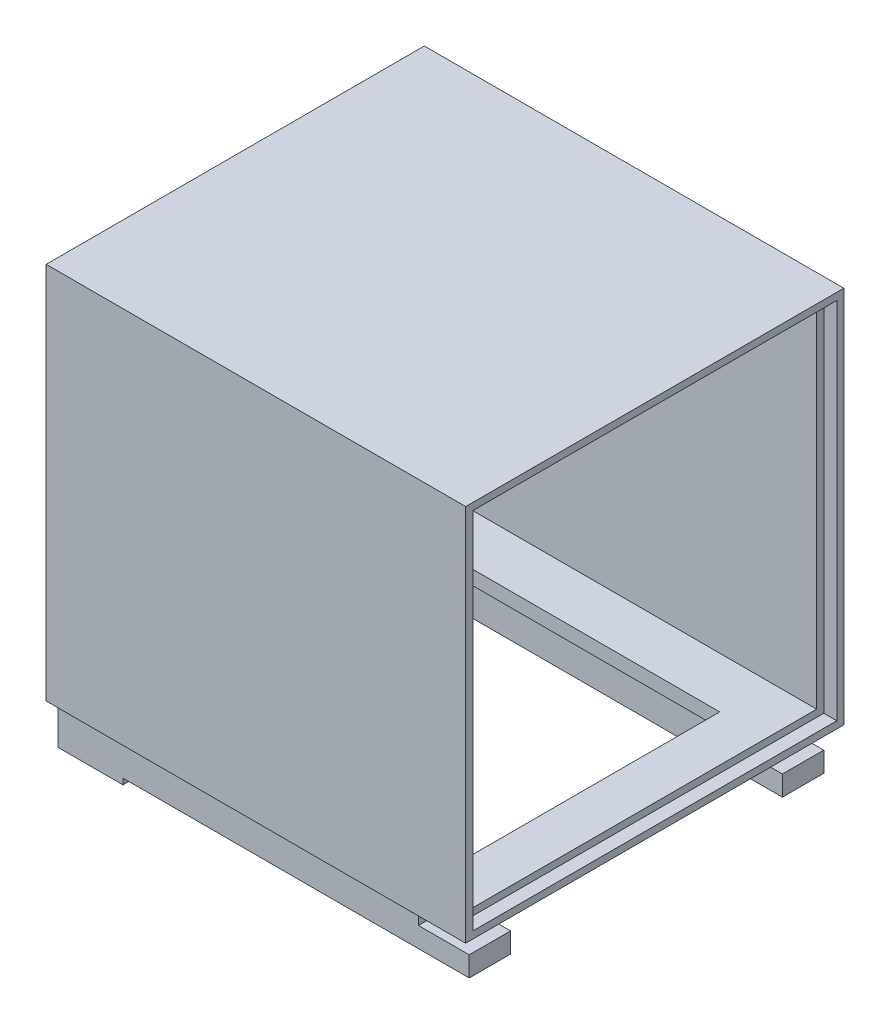
SolidWorks part; units mm, degrees
ref_plane "Front Plane" through (0, 0, 0) normal (0, 0, 1) x (1, 0, 0)
ref_plane "Top Plane" through (0, 0, 0) normal (0, 1, 0) x (1, 0, 0)
ref_plane "Right Plane" through (0, 0, 0) normal (1, 0, 0) x (0, 0, -1)
sketch "Sketch1" plane through (0, 0, 0) normal (0, 1, 0) x (1, 0, 0)
  line L1 (0, 0) -> (355, 0)
  line L2 (0, 0) -> (0, 320)
  line L3 (0, 320) -> (355, 320)
  line L4 (355, 0) -> (355, 320)
  dimension "D1" = 355
  dimension "D2" = 320
extrude "Boss-Extrude1" add sketch "Sketch1" along normal blind 320
sketch "Sketch9" plane through (355, 0, 0) normal (1, 0, 0) x (0, 0, -1)
  line L0 (320, 320) -> (320, 0) construction
  line L1 (12, 308) -> (308, 308)
  line L2 (12, 308) -> (12, 12)
  line L3 (12, 12) -> (308, 12)
  line L4 (308, 308) -> (308, 12)
  line L5 (0, 320) -> (0, 0) construction
  line L6 (0, 320) -> (320, 320) construction
  line L7 (0, 0) -> (320, 0) construction
  dimension "D1" = 12
  dimension "D2" = 12
  dimension "D3" = 12
  dimension "D4" = 12
extrude "Cut-Extrude3" cut sketch "Sketch9" against normal blind 345
sketch "Sketch10" plane through (355, 0, 0) normal (1, 0, 0) x (0, 0, -1)
  line L0 (0, 320) -> (0, 0) construction
  line L1 (6, 314) -> (314, 314)
  line L2 (6, 314) -> (6, 6)
  line L3 (6, 6) -> (314, 6)
  line L4 (314, 314) -> (314, 6)
  line L5 (320, 320) -> (320, 0) construction
  line L6 (0, 320) -> (320, 320) construction
  line L7 (0, 0) -> (320, 0) construction
  dimension "D1" = 6
  dimension "D2" = 6
  dimension "D3" = 6
  dimension "D4" = 6
extrude "Cut-Extrude4" cut sketch "Sketch10" against normal blind 11
sketch "Sketch11" plane through (0, 0, 0) normal (0, -1, 0) x (1, 0, 0)
  line L0 (355, 0) -> (355, -320) construction
  line L1 (25, -55) -> (305, -55)
  line L2 (25, -55) -> (25, -265)
  line L3 (25, -265) -> (305, -265)
  line L4 (305, -55) -> (305, -265)
  line L5 (0, 0) -> (355, 0) construction
  line L6 (355, -320) -> (0, -320) construction
  line L7 (0, -320) -> (0, 0) construction
  dimension "D1" = 50
  dimension "D2" = 55
  dimension "D3" = 55
  dimension "D4" = 25
extrude "Cut-Extrude5" cut sketch "Sketch11" against normal blind 20
sketch "Sketch12" plane through (0, 0, 0) normal (0, -1, 0) x (1, 0, 0)
  line L0 (0, 0) -> (355, 0) construction
  line L1 (20, -10) -> (305, -10)
  line L2 (20, -10) -> (20, -45)
  line L3 (20, -45) -> (305, -45)
  line L4 (305, -10) -> (305, -45)
  line L5 (305, -55) -> (25, -55) construction
  line L8 (305, -265) -> (305, -55) construction
  line L9 (0, -320) -> (0, 0) construction
  dimension "D1" = 10
  dimension "D2" = 10
  dimension "D3" = 35
  dimension "D4" = 20
extrude "Boss-Extrude4" add sketch "Sketch12" along normal blind 17
sketch "Sketch14" plane through (0, 0, 0) normal (0, -1, 0) x (1, 0, 0)
  line L0 (0, -320) -> (0, 0) construction
  line L1 (20, -275) -> (305, -275)
  line L2 (20, -275) -> (20, -310)
  line L3 (20, -310) -> (305, -310)
  line L4 (305, -275) -> (305, -310)
  line L6 (25, -265) -> (305, -265) construction
  line L7 (355, -320) -> (0, -320) construction
  line L8 (305, -265) -> (305, -55) construction
  dimension "D1" = 20
  dimension "D2" = 10
  dimension "D3" = 10
extrude "Boss-Extrude5" add sketch "Sketch14" along normal blind 17
sketch "Sketch15" plane through (0, -17, 0) normal (0, -1, 0) x (1, 0, 0)
  line L0 (305, -55) -> (25, -55) construction
  line L1 (20, -10) -> (348, -10)
  line L2 (20, -10) -> (20, -45)
  line L3 (20, -45) -> (348, -45)
  line L4 (348, -10) -> (348, -45)
  line L5 (20, -275) -> (348, -275)
  line L6 (20, -275) -> (20, -310)
  line L7 (20, -310) -> (348, -310)
  line L8 (348, -275) -> (348, -310)
  line L9 (25, -265) -> (305, -265) construction
  line L10 (355, -320) -> (0, -320) construction
  line L11 (305, -265) -> (305, -55) construction
  dimension "D1" = 10
  dimension "D2" = 10
  dimension "D3" = 10
  dimension "D4" = 43
  dimension "D5" = 43
extrude "Boss-Extrude6" add sketch "Sketch15" along normal blind 17
sketch "Sketch16" plane through (0, -34, 0) normal (0, -1, 0) x (1, 0, 0)
  line L0 (20, -310) -> (305, -310) construction
  line L1 (20, -10) -> (55, -10)
  line L2 (20, -10) -> (20, -310)
  line L3 (20, -310) -> (55, -310)
  line L4 (55, -10) -> (55, -310)
  line L5 (0, 0) -> (355, 0) construction
  line L6 (355, -320) -> (0, -320) construction
  dimension "D1" = 35
  dimension "D2" = 10
  dimension "D3" = 10
extrude "Boss-Extrude7" add sketch "Sketch16" along normal blind 5
sketch "Sketch18" plane through (0, 0, 0) normal (0, -1, 0) x (1, 0, 0)
  line L0 (20, -10) -> (20, -310) construction
  line L1 (20, -10) -> (0, -10)
  line L2 (20, -10) -> (20, -310)
  line L3 (20, -310) -> (0, -310)
  line L4 (0, -10) -> (0, -310)
  line L5 (305, -10) -> (20, -10) construction
  line L6 (20, -310) -> (55, -310) construction
  line L7 (0, -320) -> (0, 0) construction
extrude "Boss-Extrude10" add sketch "Sketch18" along normal blind 39
